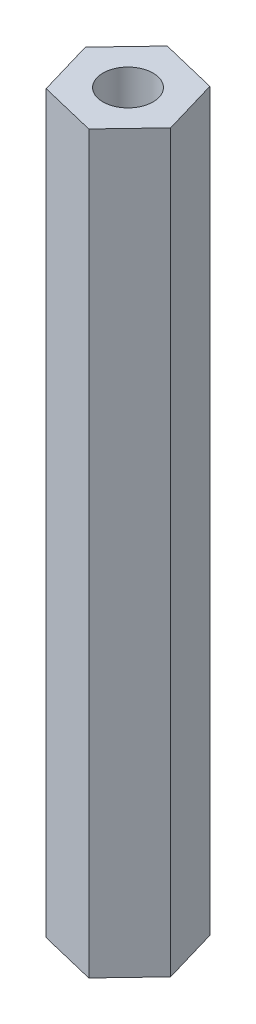
SolidWorks part; units mm, degrees
material "Thornel VCB-20 Carbon Cloth"
ref_plane "Front Plane" through (0, 0, 0) normal (0, 0, 1) x (1, 0, 0)
ref_plane "Top Plane" through (0, 0, 0) normal (0, 1, 0) x (1, 0, 0)
ref_plane "Right Plane" through (0, 0, 0) normal (1, 0, 0) x (0, 0, -1)
sketch "Sketch1" plane through (0, 0, 0) normal (0, 1, 0) x (1, 0, 0)
  line L1 (0.9773, -3.3234) -> (3.3668, -0.8153)
  line L2 (3.3668, -0.8153) -> (2.3895, 2.508)
  line L3 (2.3895, 2.508) -> (-0.9773, 3.3234)
  line L4 (-0.9773, 3.3234) -> (-3.3668, 0.8153)
  line L5 (-3.3668, 0.8153) -> (-2.3895, -2.508)
  line L6 (-2.3895, -2.508) -> (0.9773, -3.3234)
  circle A0 centre (0, 0) radius 1.5
  circle A1 centre (0, 0) radius 3 construction
  dimension "D1" = 3
  dimension "D2" = 6
extrude "Boss-Extrude1" add sketch "Sketch1" along normal mid plane 44
